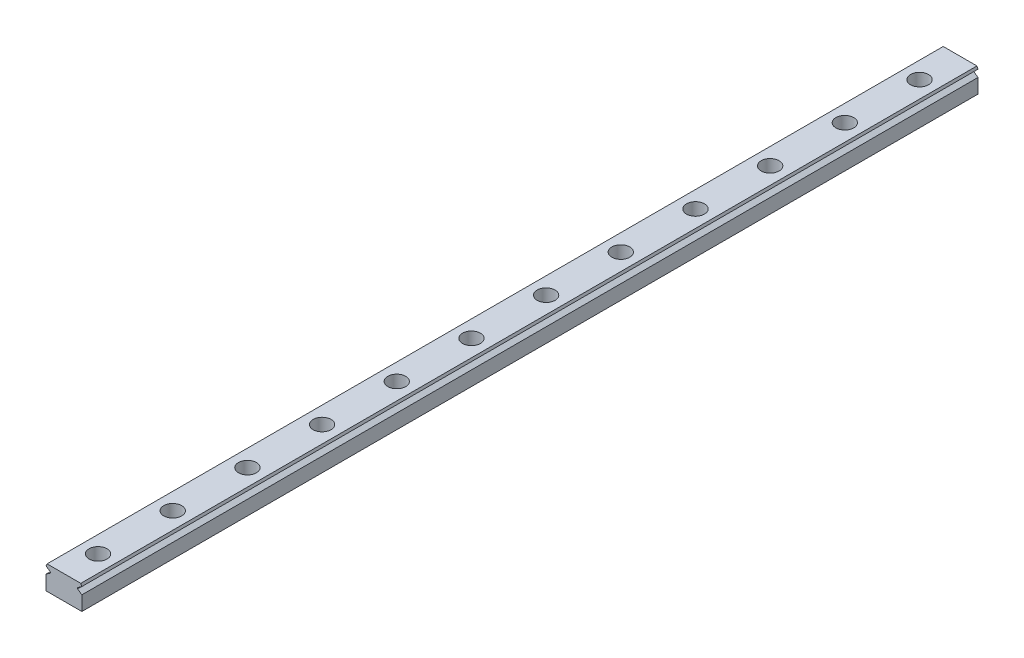
SolidWorks part; units mm, degrees
ref_plane "前视基准面" through (0, 0, 0) normal (0, 0, 1) x (1, 0, 0)
ref_plane "上视基准面" through (0, 0, 0) normal (0, 1, 0) x (1, 0, 0)
ref_plane "右视基准面" through (0, 0, 0) normal (1, 0, 0) x (0, 0, -1)
sketch "草图1" plane through (0, 0, 0) normal (0, 0, 1) x (1, 0, 0)
  line L0 (-76.7614, 75.3038) -> (-65.4736, 75.3038)
  line L1 (-65.4736, 75.3038) -> (-65.1175, 74.5402)
  line L2 (-65.1175, 74.5402) -> (-66.5493, 73.5377)
  line L3 (-66.5493, 73.5377) -> (-66.5493, 73.1469)
  line L4 (-66.5493, 73.1469) -> (-65.1175, 72.1443)
  line L5 (-65.1175, 72.1443) -> (-65.1175, 67.3038)
  line L6 (-65.1175, 67.3038) -> (-77.1175, 67.3038)
  line L7 (-77.1175, 67.3038) -> (-77.1175, 72.1443)
  line L8 (-77.1175, 72.1443) -> (-75.6857, 73.1469)
  line L9 (-75.6857, 73.1469) -> (-75.6857, 73.5377)
  line L10 (-75.6857, 73.5377) -> (-77.1175, 74.5402)
  line L11 (-77.1175, 74.5402) -> (-76.7614, 75.3038)
  point P3 (0, 0)
  point P13 (0, 0)
  point P14 (0, 0)
  point P15 (0, 0)
  point P16 (0, 0)
  point P17 (0, 0)
  point P18 (0, 0)
  point P19 (0, 0)
  point P20 (0, 0)
  point P21 (0, 0)
  point P22 (-37.7405, 48.1793)
  point P23 (-57.3103, 63.8815)
  point P24 (-61.1186, 66.4242)
  point P25 (-60.7252, 67.5608)
  point P26 (0, 0)
  point P27 (-60.5066, 67.8668)
  point P28 (-78.2362, 74.3941)
  point P29 (-77.5638, 70.7516)
  point P30 (-77.3664, 75.0741)
  point P31 (-77.1175, 72.1443)
  dimension "D1" = 125
  dimension "D2" = 125
  dimension "D3" = 100
  dimension "D4" = 100
  dimension "D5" = 125
  dimension "D6" = 8
  dimension "D7" = 12
extrude "凸台-拉伸1" add sketch "草图1" along normal blind 300
sketch "草图2" plane through (0, 75.3038, 0) normal (0, 1, 0) x (1, 0, 0)
  line L0 (-65.4736, 0) -> (-76.7614, 0) construction
  line L1 (-71.1175, 0) -> (-71.1175, -300) construction
  line L2 (-65.4736, -300) -> (-76.7614, -300) construction
  circle A0 centre (-71.1175, -13.5781) radius 3
  circle A1 centre (-71.1175, -38.5781) radius 3
  circle A2 centre (-71.1175, -63.5781) radius 3
  circle A3 centre (-71.1175, -88.5781) radius 3
  circle A4 centre (-71.1175, -113.5781) radius 3
  circle A5 centre (-71.1175, -138.5781) radius 3
  circle A6 centre (-71.1175, -163.5781) radius 3
  circle A7 centre (-71.1175, -188.5781) radius 3
  circle A8 centre (-71.1175, -213.5781) radius 3
  circle A9 centre (-71.1175, -238.5781) radius 3
  circle A10 centre (-71.1175, -263.5781) radius 3
  circle A11 centre (-71.1175, -288.5781) radius 3
  point P0 (-71.1175, 0)
  point P29 (0, 0)
  point P30 (-71.1175, -36.4797)
  point P33 (-71.1175, -288.5781)
  dimension "D1" = 25
  dimension "D2" = 25
  dimension "D3" = 25
  dimension "D4" = 25
  dimension "D5" = 25
  dimension "D11" = 25
  dimension "D6" = 25
  dimension "D7" = 25
  dimension "D8" = 25
  dimension "D9" = 25
  dimension "D10" = 25
extrude "切除-拉伸1" cut sketch "草图2" against normal blind 4.5
sketch "草图5" plane through (0, 75.3038, 0) normal (0, 1, 0) x (1, 0, 0)
  circle A0 centre (-71.1175, -13.5781) radius 1.75
  circle A1 centre (-71.1175, -38.5781) radius 1.75
  circle A2 centre (-71.1175, -63.5781) radius 1.75
  circle A3 centre (-71.1175, -88.5781) radius 1.75
  circle A4 centre (-71.1175, -113.5781) radius 1.75
  circle A5 centre (-71.1175, -138.5781) radius 1.75
  circle A6 centre (-71.1175, -163.5781) radius 1.75
  circle A7 centre (-71.1175, -188.5781) radius 1.75
  circle A8 centre (-71.1175, -213.5781) radius 1.75
  circle A9 centre (-71.1175, -238.5781) radius 1.75
  circle A10 centre (-71.1175, -263.5781) radius 1.75
  circle A11 centre (-71.1175, -288.5781) radius 1.75
extrude "切除-拉伸2" cut sketch "草图5" against normal blind 8
